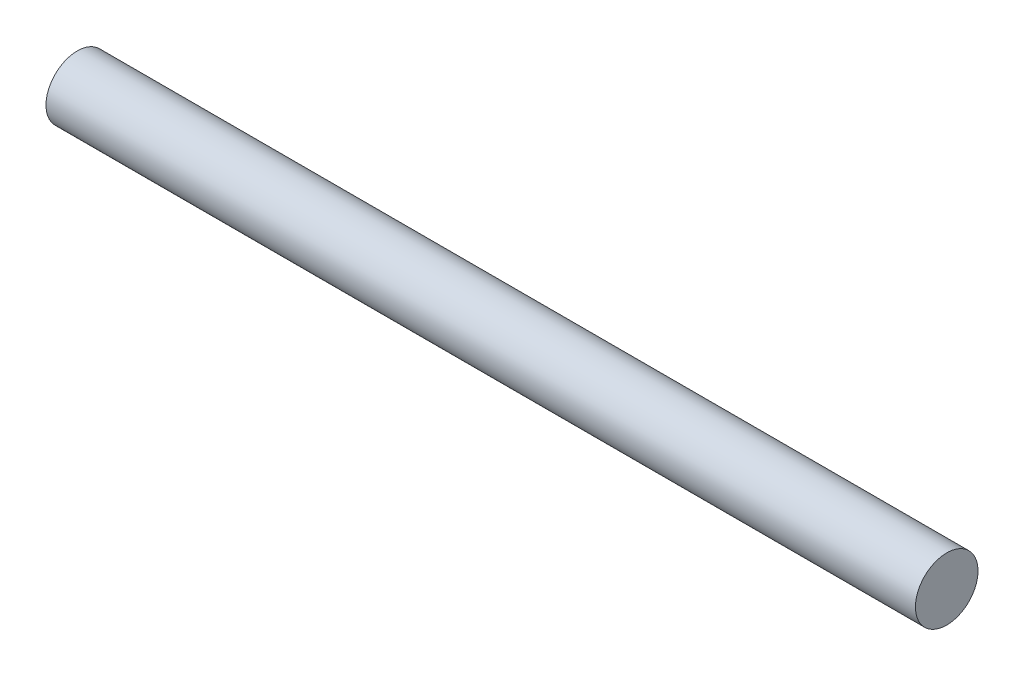
SolidWorks part; units mm, degrees
ref_plane "Front Plane" through (0, 0, 0) normal (0, 0, 1) x (1, 0, 0)
ref_plane "Top Plane" through (0, 0, 0) normal (0, 1, 0) x (1, 0, 0)
ref_plane "Right Plane" through (0, 0, 0) normal (1, 0, 0) x (0, 0, -1)
sketch "Sketch1" plane through (0, 0, 0) normal (0, 0, 1) x (1, 0, 0)
  line L0 (-250, 0) -> (250, 0) construction
  line L1 (-250, 0) -> (-250, 18)
  line L2 (-250, 18) -> (250, 18)
  line L3 (250, 18) -> (250, 0)
  line L4 (-250, 0) -> (250, 0)
  point P4 (0, 0)
  dimension "D1" = 500
  dimension "D2" = 18
revolve "Revolve1" add sketch "Sketch1" angle 360 about L0
sketch "Sketch2" plane through (0, 0, 0) normal (0, 0, 1) x (1, 0, 0)
  line L0 (-275, 0) -> (275, 0) construction
  point P4 (0, 0)
  dimension "D1" = 550
